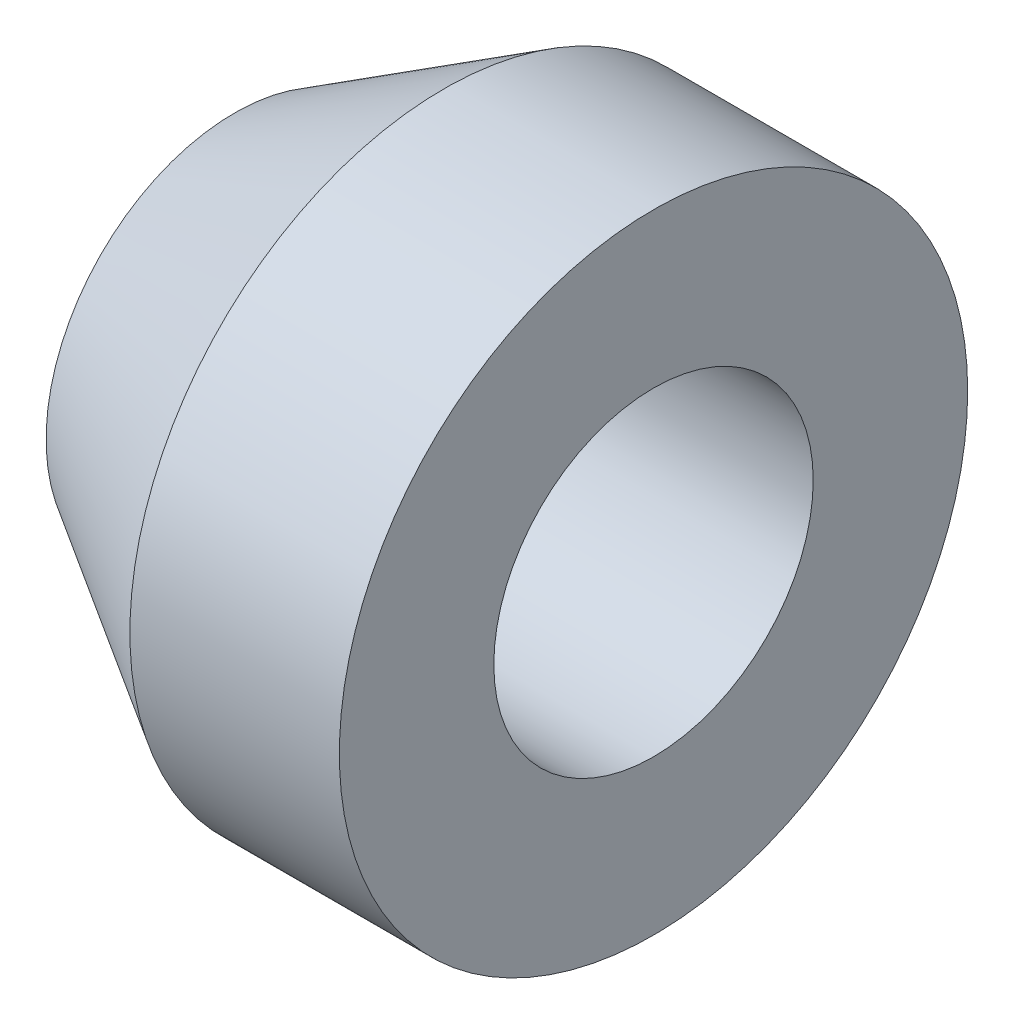
SolidWorks part; units mm, degrees
ref_plane "Front Plane" through (0, 0, 0) normal (0, 0, 1) x (1, 0, 0)
ref_plane "Top Plane" through (0, 0, 0) normal (0, 1, 0) x (1, 0, 0)
ref_plane "Right Plane" through (0, 0, 0) normal (1, 0, 0) x (0, 0, -1)
sketch "Sketch1" plane through (0, 0, 0) normal (1, 0, 0) x (0, 0, -1)
  circle A0 centre (0, 0) radius 3
  circle A1 centre (0, 0) radius 1.525
  dimension "D1" = 6
  dimension "D2" = 3.05
extrude "Boss-Extrude1" add sketch "Sketch1" along normal blind 4 contours A0
chamfer "Chamfer1" distance 1.2 distance2 2 1 edges at (0, 0, -3)
